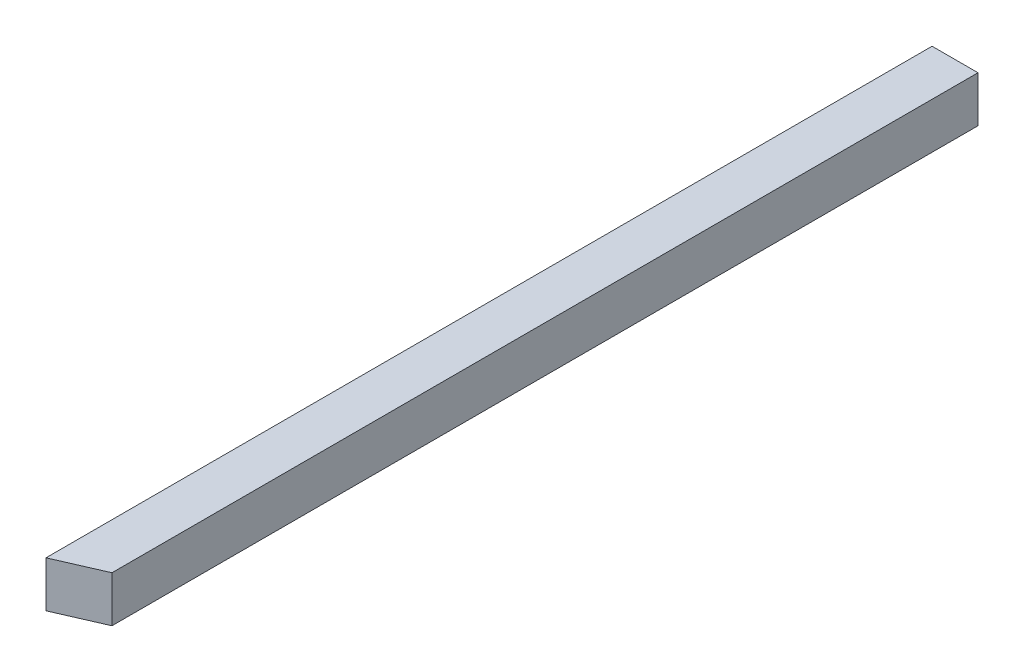
SolidWorks part; units mm, degrees
ref_plane "Front Plane" through (0, 0, 0) normal (0, 0, 1) x (1, 0, 0)
ref_plane "Top Plane" through (0, 0, 0) normal (0, 1, 0) x (1, 0, 0)
ref_plane "Right Plane" through (0, 0, 0) normal (1, 0, 0) x (0, 0, -1)
sketch "Sketch1" plane through (0, 0, 0) normal (0, 0, 1) x (1, 0, 0)
  line L1 (0, 0) -> (10, 0)
  line L2 (0, 0) -> (0, -10)
  line L3 (0, -10) -> (10, -10)
  line L4 (10, 0) -> (10, -10)
  dimension "D1" = 10
extrude "Boss-Extrude1" add sketch "Sketch1" along normal blind 300
sketch "Sketch2" plane through (0, -10, 0) normal (0, -1, 0) x (1, 0, 0)
  line L0 (0, 192.9085) -> (10, 188.5467)
  line L1 (0, 300) -> (0, 0) construction
  line L2 (10, 300) -> (10, 0) construction
  line L3 (10, 188.5467) -> (10, 300)
  line L4 (10, 300) -> (0, 300)
  line L5 (0, 300) -> (0, 192.9085)
extrude "Cut-Extrude1" cut sketch "Sketch2" against normal through all both and the other way through all
